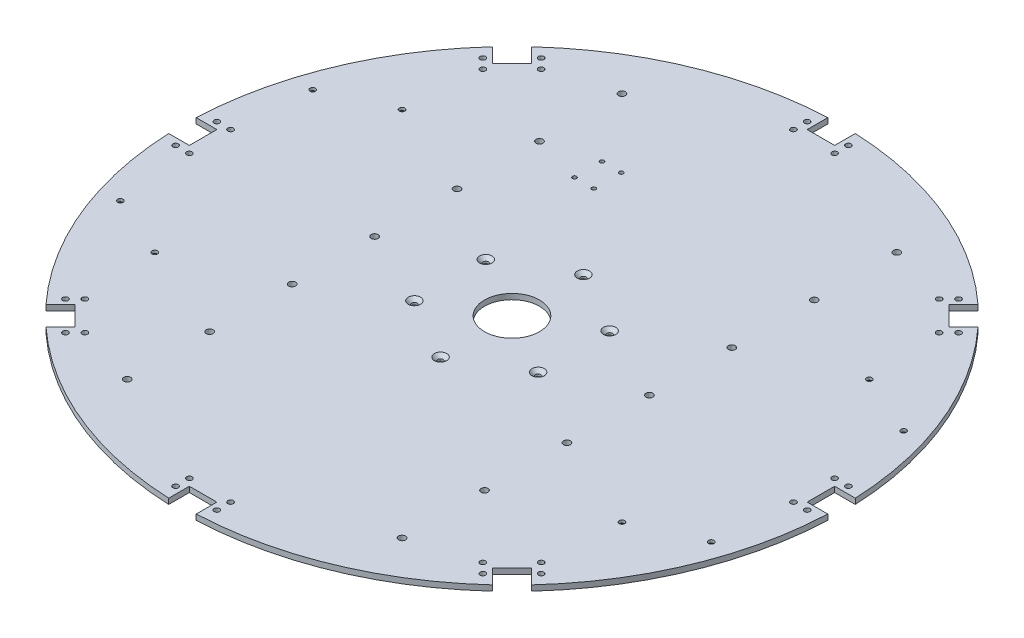
SolidWorks part; units mm, degrees
material "S-玻璃纤维"
ref_plane "前视基准面" through (0, 0, 0) normal (0, 0, 1) x (1, 0, 0)
ref_plane "上视基准面" through (0, 0, 0) normal (0, 1, 0) x (1, 0, 0)
ref_plane "右视基准面" through (0, 0, 0) normal (1, 0, 0) x (0, 0, -1)
sketch "草图1" plane through (0, 0, 0) normal (0, 1, 0) x (1, 0, 0)
  circle A0 centre (0, 0) radius 240
  dimension "D1" = 480
extrude "凸台-拉伸1" add sketch "草图1" along normal blind 4
sketch "草图2" plane through (0, 0, 0) normal (0, 1, 0) x (1, 0, 0)
  line L0 (-45.0333, 26) -> (-45.0333, 118.9876) construction
  line L1 (45.0333, 26) -> (0, 52) construction
  line L2 (0, 52) -> (-45.0333, 26) construction
  line L3 (-45.0333, 26) -> (-45.0333, -26) construction
  line L4 (-45.0333, -26) -> (0, -52) construction
  line L5 (0, -52) -> (45.0333, -26) construction
  line L6 (45.0333, -26) -> (45.0333, 26) construction
  line L7 (100, 0) -> (100, 218.1742) construction
  line L8 (100, 0) -> (100, -218.1742) construction
  line L9 (0, 0) -> (0, -180.5982) construction
  line L10 (-50.5, 110) -> (-64.5, 130) construction
  line L11 (0, 0) -> (-292.1777, 0) construction
  circle A0 centre (0, 0) radius 45.0333 construction
  circle A1 centre (-45.0333, 26) radius 2
  circle A2 centre (0, 52) radius 2
  circle A3 centre (45.0333, 26) radius 2
  circle A4 centre (45.0333, -26) radius 2
  circle A5 centre (0, -52) radius 2
  circle A6 centre (-45.0333, -26) radius 2
  circle A14 centre (-64.5, 130) radius 1.5
  circle A15 centre (100, 0) radius 2.5
  circle A16 centre (0, 0) radius 240 construction
  circle A17 centre (100, 60) radius 2.5
  circle A18 centre (100, 120) radius 2.5
  circle A19 centre (100, 180) radius 2.5
  circle A20 centre (100, -60) radius 2.5
  circle A21 centre (100, -120) radius 2.5
  circle A22 centre (100, -180) radius 2.5
  circle A23 centre (-100, -180) radius 2.5
  circle A24 centre (-100, -120) radius 2.5
  circle A25 centre (-100, -60) radius 2.5
  circle A26 centre (-100, 180) radius 2.5
  circle A27 centre (-100, 120) radius 2.5
  circle A28 centre (-100, 60) radius 2.5
  circle A29 centre (-100, 0) radius 2.5
  circle A30 centre (-50.5, 130) radius 1.5
  circle A31 centre (-64.5, 110) radius 1.5
  circle A32 centre (-50.5, 110) radius 1.5
  circle A33 centre (0, 0) radius 20
  circle A34 centre (170, 90) radius 2
  circle A35 centre (170, -90) radius 2
  circle A36 centre (-170, -90) radius 2
  circle A37 centre (-170, 90) radius 2
  circle A38 centre (215, -70) radius 2
  circle A39 centre (215, 70) radius 2
  circle A40 centre (-215, 70) radius 2
  circle A41 centre (-215, -70) radius 2
  point P60 (-57.5, 120)
  dimension "D2" = 4
  dimension "D4" = 100
  dimension "D5" = 5
  dimension "D10" = 3
  dimension "D15" = 40
  dimension "D16" = 4
  dimension "D22" = 4
  dimension "D1" = 52
  dimension "D6" = 4
  dimension "D7" = 60
  dimension "D9" = 60
  dimension "D11" = 14
  dimension "D12" = 20
  dimension "D13" = 57.5
  dimension "D14" = 120
  dimension "D17" = 180
  dimension "D18" = 90
  dimension "D19" = 170
  dimension "D20" = 20
  dimension "D21" = 45
  dimension "D8" = 4
  dimension "D3" = 6
extrude "切除-拉伸2" cut sketch "草图2" along normal through all
chamfer "倒角1" distance 2.5 angle 45 6 edges at (0, 4, 54) (45.0333, 4, 28) (45.0333, 4, -24) (0, 4, -50) (-45.0333, 4, -24) (-45.0333, 4, 28)
sketch "草图3" plane through (0, 0, 0) normal (0, 1, 0) x (1, 0, 0)
  line L0 (0, 0) -> (0, 240) construction
  line L1 (-10, 239.7916) -> (-10, 224.7916)
  line L2 (-10, 224.7916) -> (10, 224.7916)
  line L3 (10, 224.7916) -> (10, 239.7916)
  line L4 (166.0227, 151.8806) -> (176.6293, 162.4872)
  line L5 (151.8806, 166.0227) -> (166.0227, 151.8806)
  line L6 (162.4872, 176.6293) -> (151.8806, 166.0227)
  line L7 (224.7916, -10) -> (239.7916, -10)
  line L8 (224.7916, 10) -> (224.7916, -10)
  line L9 (239.7916, 10) -> (224.7916, 10)
  line L10 (151.8806, -166.0227) -> (162.4872, -176.6293)
  line L11 (166.0227, -151.8806) -> (151.8806, -166.0227)
  line L12 (176.6293, -162.4872) -> (166.0227, -151.8806)
  line L13 (-10, -224.7916) -> (-10, -239.7916)
  line L14 (10, -224.7916) -> (-10, -224.7916)
  line L15 (10, -239.7916) -> (10, -224.7916)
  line L16 (-166.0227, -151.8806) -> (-176.6293, -162.4872)
  line L17 (-151.8806, -166.0227) -> (-166.0227, -151.8806)
  line L18 (-162.4872, -176.6293) -> (-151.8806, -166.0227)
  line L19 (-224.7916, 10) -> (-239.7916, 10)
  line L20 (-224.7916, -10) -> (-224.7916, 10)
  line L21 (-239.7916, -10) -> (-224.7916, -10)
  line L22 (-151.8806, 166.0227) -> (-162.4872, 176.6293)
  line L23 (-166.0227, 151.8806) -> (-151.8806, 166.0227)
  line L24 (-176.6293, 162.4872) -> (-166.0227, 151.8806)
  circle A0 centre (151.8806, 173.0938) radius 2
  circle A1 centre (0, 0) radius 240 construction
  arc A2 (10, 239.7916) -> (-10, 239.7916) centre (0, 0) ccw
  arc A3 (176.6293, 162.4872) -> (162.4872, 176.6293) centre (0, 0) ccw
  arc A4 (239.7916, -10) -> (239.7916, 10) centre (0, 0) ccw
  arc A5 (162.4872, -176.6293) -> (176.6293, -162.4872) centre (0, 0) ccw
  circle A6 centre (-15, 229.7916) radius 2
  circle A7 centre (-15, 219.7916) radius 2
  circle A8 centre (15, 219.7916) radius 2
  circle A9 centre (15, 229.7916) radius 2
  circle A10 centre (144.8095, 166.0227) radius 2
  circle A11 centre (173.0938, 151.8806) radius 2
  circle A12 centre (166.0227, 144.8095) radius 2
  circle A13 centre (229.7916, 15) radius 2
  circle A14 centre (219.7916, 15) radius 2
  circle A15 centre (229.7916, -15) radius 2
  circle A16 centre (219.7916, -15) radius 2
  circle A17 centre (173.0938, -151.8806) radius 2
  circle A18 centre (166.0227, -144.8095) radius 2
  circle A19 centre (151.8806, -173.0938) radius 2
  circle A20 centre (144.8095, -166.0227) radius 2
  circle A21 centre (15, -229.7916) radius 2
  circle A22 centre (15, -219.7916) radius 2
  circle A23 centre (-15, -229.7916) radius 2
  circle A24 centre (-15, -219.7916) radius 2
  circle A25 centre (-151.8806, -173.0938) radius 2
  circle A26 centre (-144.8095, -166.0227) radius 2
  circle A27 centre (-173.0938, -151.8806) radius 2
  circle A28 centre (-166.0227, -144.8095) radius 2
  circle A29 centre (-229.7916, -15) radius 2
  circle A30 centre (-219.7916, -15) radius 2
  circle A31 centre (-229.7916, 15) radius 2
  circle A32 centre (-219.7916, 15) radius 2
  circle A33 centre (-173.0938, 151.8806) radius 2
  circle A34 centre (-166.0227, 144.8095) radius 2
  circle A35 centre (-151.8806, 173.0938) radius 2
  circle A36 centre (-144.8095, 166.0227) radius 2
  circle A37 centre (0, 0) radius 230.2806 construction
  arc A38 (-176.6293, 162.4872) -> (-162.4872, 176.6293) centre (0, 0) cw
  arc A39 (-239.7916, 10) -> (-239.7916, -10) centre (0, 0) ccw
  arc A40 (-10, -239.7916) -> (10, -239.7916) centre (0, 0) ccw
  arc A41 (-176.6293, -162.4872) -> (-162.4872, -176.6293) centre (0, 0) ccw
  dimension "D4" = 4
  dimension "D1" = 15
  dimension "D2" = 20
  dimension "D3" = 8
  dimension "D5" = 10
  dimension "D6" = 5
  dimension "D7" = 5
  dimension "D8" = 8
extrude "切除-拉伸3" cut sketch "草图3" along normal through all
chamfer "倒角2" distance 2 angle 45 8 edges at (-215, 0, -68) (-170, 0, -92) (-215, 0, 68) (-170, 0, 88) (170, 0, -88) (170, 0, 92) (215, 0, -72) (215, 0, 72)
